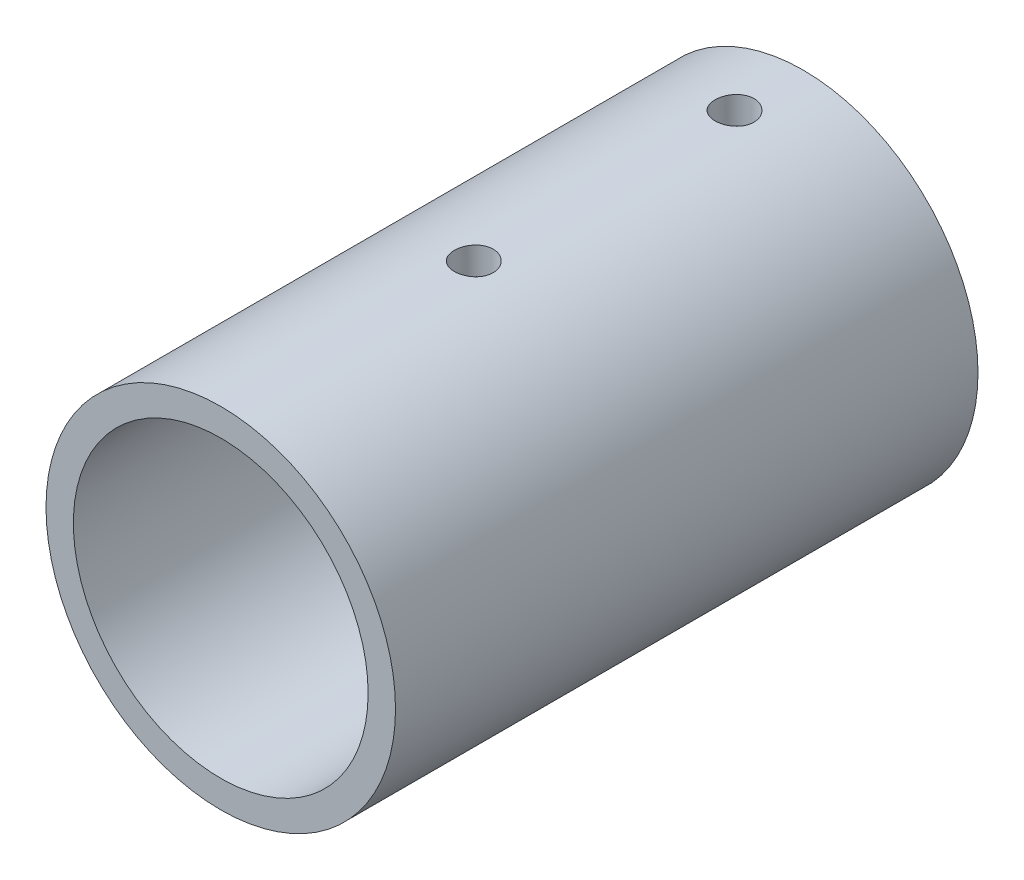
SolidWorks part; units mm, degrees
ref_plane "Front Plane" through (0, 0, 0) normal (0, 0, 1) x (1, 0, 0)
ref_plane "Top Plane" through (0, 0, 0) normal (0, 1, 0) x (1, 0, 0)
ref_plane "Right Plane" through (0, 0, 0) normal (1, 0, 0) x (0, 0, -1)
sketch "Sketch1" plane through (0, 0, 0) normal (0, 0, 1) x (1, 0, 0)
  circle A0 centre (0, 0) radius 45
  dimension "D1" = 90
extrude "Boss-Extrude1" add sketch "Sketch1" along normal blind 150
sketch "Sketch2" plane through (0, 0, 150) normal (0, 0, 1) x (1, 0, 0)
  circle A0 centre (0, 0) radius 31.85
  dimension "D1" = 63.7
extrude "Cut-Extrude1" cut sketch "Sketch2" against normal through all
sketch "Sketch3" plane through (0, 0, 150) normal (0, 0, 1) x (1, 0, 0)
  circle A0 centre (0, 0) radius 37.95
  dimension "D1" = 75.9
extrude "Cut-Extrude2" cut sketch "Sketch3" against normal blind 140
sketch "Sketch8" plane through (0, 0, 0) normal (0, 1, 0) x (1, 0, 0)
  circle A0 centre (0, -17.7) radius 5
  circle A1 centre (0, -84.85) radius 5
  dimension "D3" = 10
  dimension "D1" = 17.7
  dimension "D2" = 67.15
extrude "Cut-Extrude5" cut sketch "Sketch8" against normal through all both and the other way through all
